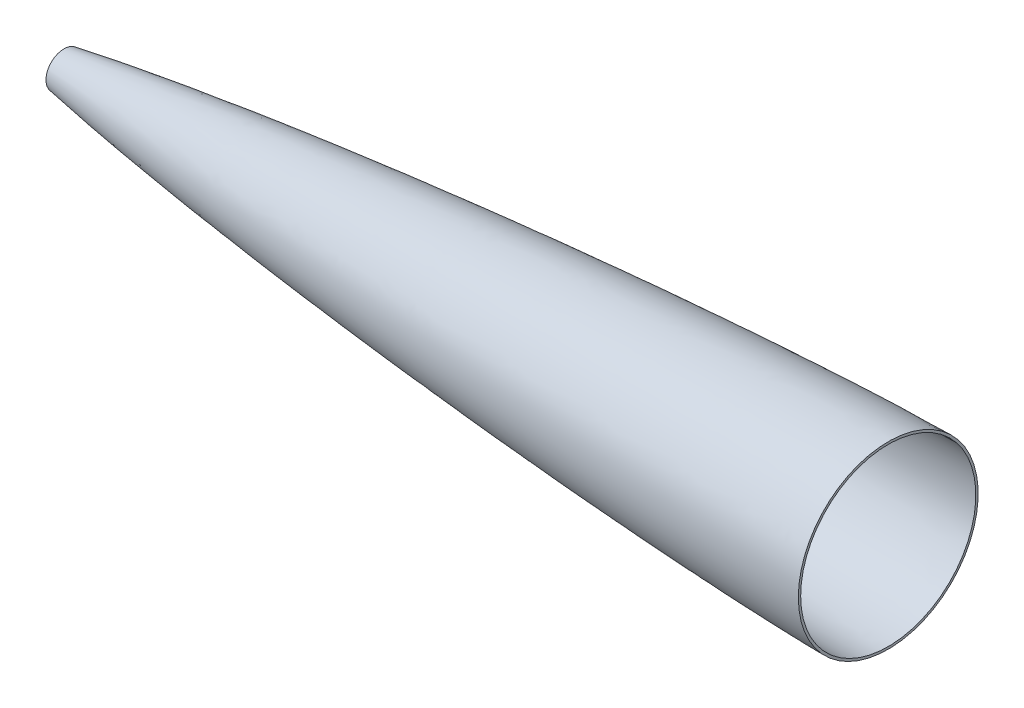
SolidWorks part; units mm, degrees
ref_plane "Front Plane" through (0, 0, 0) normal (0, 0, 1) x (1, 0, 0)
ref_plane "Top Plane" through (0, 0, 0) normal (0, 1, 0) x (1, 0, 0)
ref_plane "Right Plane" through (0, 0, 0) normal (1, 0, 0) x (0, 0, -1)
sketch "Sketch1" plane through (0, 0, 0) normal (0, 0, 1) x (1, 0, 0)
  line L4 (0, 16.3897) -> (991.2216, 16.3897) construction
  line L5 (63.8441, 29.6409) -> (63.5, 29.6409)
  line L6 (63.5, 29.6409) -> (63.5, 31.592)
  line L8 (762, 92.5897) -> (762, 90.6085)
  spline S0 degree 4 poles (0.6349, 16.8768) (0.7287, 16.9302) (0.9179, 17.0341) (1.2372, 17.1963) (1.749, 17.4347) (2.4703, 17.7443) (3.5777, 18.1792) (5.3468, 18.81) (8.2661, 19.7469) (12.0215, 20.8224) (16.4352, 21.9779) (21.9622, 23.3224) (27.1046, 24.4917) (32.0716, 25.5657) (36.6751, 26.5213) (40.1312, 27.2204) (43.4101, 27.8689) (46.4854, 28.4658) (49.594, 29.058) (52.6488, 29.6306) (55.8066, 30.2121) (58.7586, 30.7487) (62.6285, 31.4399) (65.666, 31.974) (70.6985, 32.847) (74.7504, 33.5312) (80.786, 34.5406) (87.4753, 35.6288) (96.3257, 37.0367) (106.8615, 38.6563) (118.2247, 40.3506) (130.244, 42.0843) (142.3082, 43.7744) (154.3565, 45.4147) (166.4235, 47.0148) (178.4884, 48.5741) (193.5799, 50.4777) (211.696, 52.6919) (232.8443, 55.1817) (257.0263, 57.9095) (281.2208, 60.5285) (305.4259, 63.0452) (329.641, 65.4648) (353.8652, 67.7913) (378.0978, 70.0277) (402.3384, 72.1764) (432.6486, 74.7544) (462.9706, 77.1899) (493.3036, 79.4835) (523.6472, 81.6321) (547.9282, 83.2621) (578.2869, 85.1849) (614.7292, 87.3009) (651.1858, 89.1579) (687.6567, 90.7085) (715.9489, 91.6728) (734.0694, 92.1637) (748.0961, 92.4456) (756.041, 92.5515) (760.0136, 92.5853) (762, 92.5897) knots 0 0 0 0 0 0.000563 0.001126 0.001869 0.002947 0.004659 0.007335 0.011671 0.018947 0.025047 0.031147 0.041362 0.046469 0.051577 0.055679 0.059782 0.063885 0.067987 0.07209 0.076193 0.080295 0.084398 0.090458 0.096519 0.10258 0.10864 0.120761 0.132883 0.14876 0.164638 0.180516 0.196394 0.212272 0.228149 0.244027 0.259905 0.291661 0.323416 0.355172 0.386927 0.418683 0.450438 0.482194 0.513949 0.545705 0.577461 0.640972 0.672727 0.704483 0.736238 0.767994 0.831505 0.895016 0.926772 0.958527 0.979264 0.989632 1 1 1 1 1 construction
  spline S1 degree 4 poles (63.5, 31.592) (64.547, 31.7767) (66.5925, 32.1348) (70.6985, 32.847) (74.7504, 33.5312) (80.786, 34.5406) (87.4753, 35.6288) (96.3257, 37.0367) (106.8615, 38.6563) (118.2247, 40.3506) (130.244, 42.0843) (142.3082, 43.7744) (154.3565, 45.4147) (166.4235, 47.0148) (178.4884, 48.5741) (193.5799, 50.4777) (211.696, 52.6919) (232.8443, 55.1817) (257.0263, 57.9095) (281.2208, 60.5285) (305.4259, 63.0452) (329.641, 65.4648) (353.8652, 67.7913) (378.0978, 70.0277) (402.3384, 72.1764) (432.6486, 74.7544) (462.9706, 77.1899) (493.3036, 79.4835) (523.6472, 81.6321) (547.9282, 83.2621) (578.2869, 85.1849) (614.7292, 87.3009) (651.1858, 89.1579) (687.6567, 90.7085) (715.9489, 91.6728) (734.0694, 92.1637) (748.0961, 92.4456) (756.041, 92.5515) (760.0136, 92.5853) (762, 92.5897) knots 0.084398 0.084398 0.084398 0.084398 0.084398 0.090458 0.096519 0.10258 0.10864 0.120761 0.132883 0.14876 0.164638 0.180516 0.196394 0.212272 0.228149 0.244027 0.259905 0.291661 0.323416 0.355172 0.386927 0.418683 0.450438 0.482194 0.513949 0.545705 0.577461 0.640972 0.672727 0.704483 0.736238 0.767994 0.831505 0.895016 0.926772 0.958527 0.979264 0.989632 1 1 1 1 1
  spline S2 degree 1 poles (63.8441, 29.6409) (762.0044, 90.6085) knots 0 0 1 1 construction
  spline S3 degree 3 poles (63.8441, 29.6409) (64.257, 29.7137) (65.0708, 29.8568) (66.7939, 30.1579) (69.2241, 30.5797) (72.0516, 31.0649) (74.5912, 31.4944) (77.2638, 31.9426) (80.0495, 32.4061) (82.7701, 32.8537) (86.34, 33.4347) (90.8185, 34.1534) (98.0782, 35.2996) (110.6669, 37.2343) (128.7593, 39.8895) (172.1568, 45.9177) (237.4312, 53.9365) (324.6213, 63.1641) (411.9389, 71.1827) (499.3506, 78.0943) (572.2607, 82.9223) (630.6238, 86.1495) (674.4116, 88.2078) (710.915, 89.5586) (736.4666, 90.2375) (751.0689, 90.5082) (758.3635, 90.6004) (762.0015, 90.6085) (762.0033, 90.6085) (762.0044, 90.6085) knots 0.084398 0.084398 0.084398 0.084398 0.086186 0.087974 0.091551 0.095128 0.098704 0.102281 0.105857 0.109434 0.11301 0.120164 0.127317 0.141623 0.170236 0.198848 0.313298 0.427749 0.542199 0.656649 0.771099 0.828325 0.88555 0.942775 0.971387 0.985694 0.999993 0.999996 1 1 1 1 only from (63.8441, 29.6409) to (762, 90.6085)
  dimension "D2" = 698.5
  dimension "D3" = 76.2
  dimension "D1" = 1.9812
revolve "Revolve1" add sketch "Sketch1" angle 360 about L4
